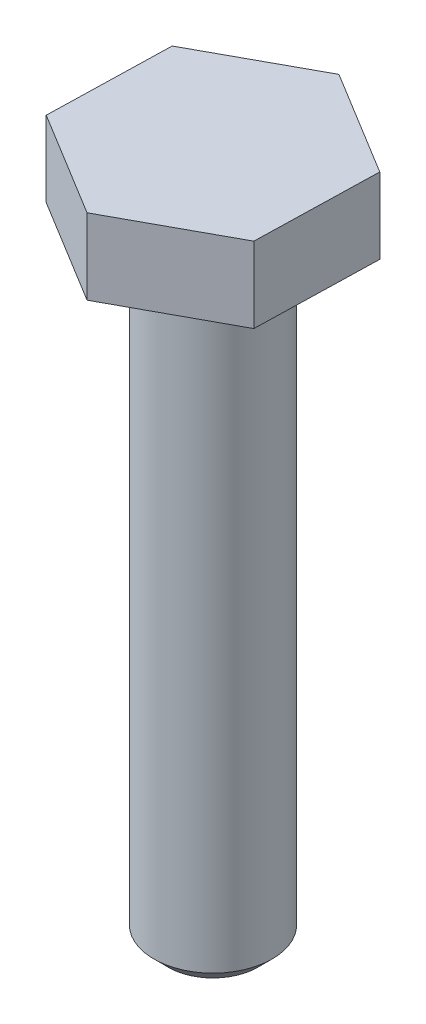
SolidWorks part; units mm, degrees
material "Plain Carbon Steel"
ref_plane "Front Plane" through (0, 0, 0) normal (0, 0, 1) x (1, 0, 0)
ref_plane "Top Plane" through (0, 0, 0) normal (0, 1, 0) x (1, 0, 0)
ref_plane "Right Plane" through (0, 0, 0) normal (1, 0, 0) x (0, 0, -1)
sketch "Sketch1" plane through (0, 0, 0) normal (0, 1, 0) x (1, 0, 0)
  line L1 (5.6315, -3.4401) -> (5.795, 3.157)
  line L2 (5.795, 3.157) -> (0.1634, 6.5971)
  line L3 (0.1634, 6.5971) -> (-5.6315, 3.4401)
  line L4 (-5.6315, 3.4401) -> (-5.795, -3.157)
  line L5 (-5.795, -3.157) -> (-0.1634, -6.5971)
  line L6 (-0.1634, -6.5971) -> (5.6315, -3.4401)
  circle A0 centre (0, 0) radius 5.715 construction
  dimension "D1" = 11.43
extrude "Boss-Extrude1" add sketch "Sketch1" along normal blind 4.064
sketch "Sketch2" plane through (0, 0, 0) normal (0, -1, 0) x (-1, 0, 0)
  circle A0 centre (0, 0) radius 3.175
  dimension "D1" = 6.35
extrude "Boss-Extrude2" add sketch "Sketch2" along normal blind 33.02
chamfer "Chamfer1" distance 0.762 angle 45 1 edges at (0, -33.02, -3.175)
